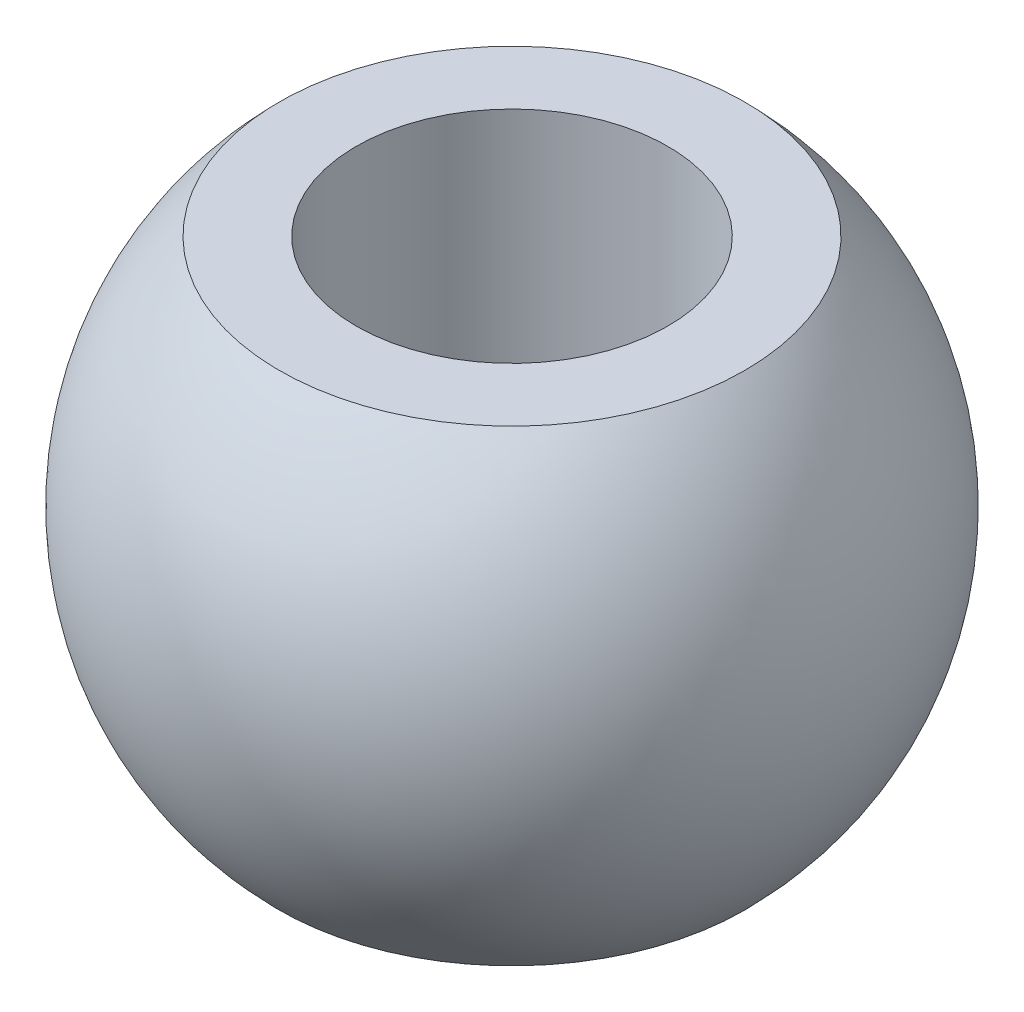
SolidWorks part; units mm, degrees
material "Polyetheretherketone (PEEK)"
ref_plane "Front Plane" through (0, 0, 0) normal (0, 0, 1) x (1, 0, 0)
ref_plane "Top Plane" through (0, 0, 0) normal (0, 1, 0) x (1, 0, 0)
ref_plane "Right Plane" through (0, 0, 0) normal (1, 0, 0) x (0, 0, -1)
ref_plane "Plane1" through (0, 0, 0) normal (0, 0, -1) x (-1, 0, 0)
sketch "Sketch1" plane through (0, 0, 0) normal (0, 0, -1) x (-1, 0, 0)
  line L0 (-4.4802, -4.5) -> (-3, -4.5)
  line L1 (-3, -4.5) -> (-3, 4.5)
  line L2 (-3, 4.5) -> (-4.4802, 4.5)
  line L3 (0, -4.5) -> (0, 4.5) construction
  arc A0 (-4.4802, 4.5) -> (-4.4802, -4.5) centre (0, 0) ccw
revolve "Revolve1" add sketch "Sketch1" angle 360 about L3
